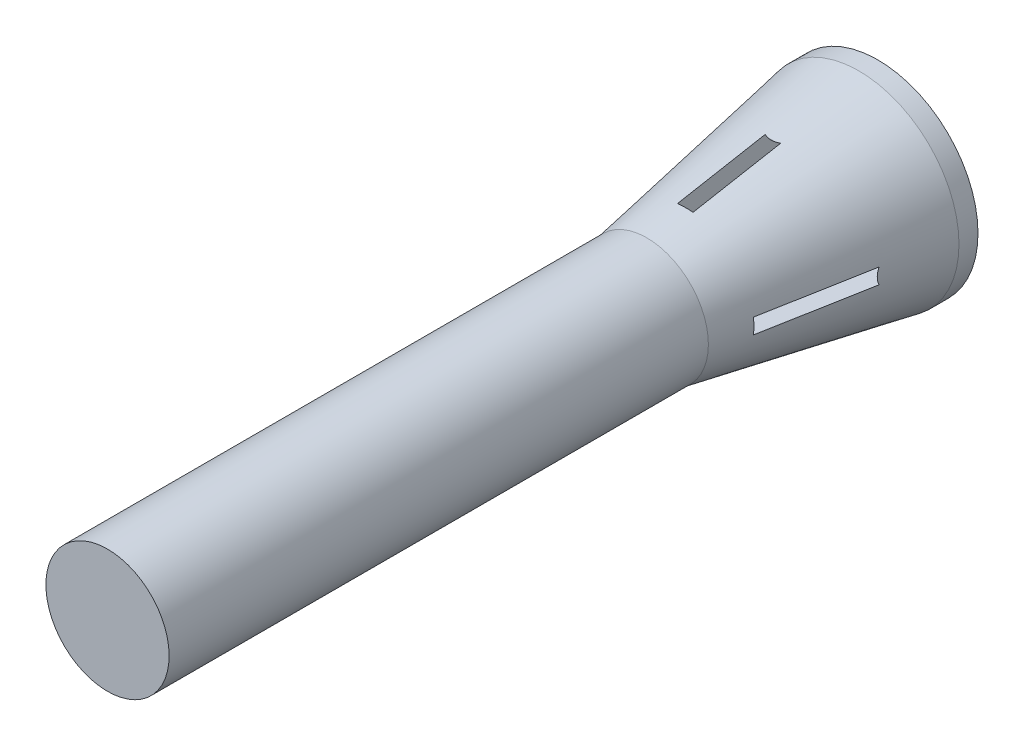
SolidWorks part; units mm, degrees
ref_plane "Plan de face" through (0, 0, 0) normal (0, 0, 1) x (1, 0, 0)
ref_plane "Plan de dessus" through (0, 0, 0) normal (0, 1, 0) x (1, 0, 0)
ref_plane "Plan de droite" through (0, 0, 0) normal (1, 0, 0) x (0, 0, -1)
sketch "Esquisse1" plane through (0, 0, 0) normal (1, 0, 0) x (0, 0, -1)
  line L0 (73.2699, 13.7287) -> (72.0362, 13.7287)
  line L1 (72.0362, 13.7287) -> (58.2699, 11.2287)
  line L2 (58.2699, 11.2287) -> (23.2699, 11.2287)
  line L3 (23.2699, 11.2287) -> (23.2699, 7.2287)
  line L4 (23.2699, 7.2287) -> (63.2699, 7.2287)
  line L5 (63.2699, 7.2287) -> (63.2699, 10.2287)
  line L6 (63.2699, 10.2287) -> (73.2699, 10.2287)
  line L7 (73.2699, 10.2287) -> (73.2699, 13.7287)
  dimension "D1" = 3.5
  dimension "D2" = 3
  dimension "D3" = 50
  dimension "D4" = 15
  dimension "D5" = 4
  dimension "D6" = 40
revolve "Révolution1" add sketch "Esquisse1" angle 360 about L4
sketch "Esquisse12" plane through (0, 0, -73.2699) normal (0, 0, -1) x (-1, 0, 0)
  line L0 (0.5, 7.7287) -> (6.0527, 7.7287)
  line L1 (-0.5, 12.6932) -> (0.5, 12.6932)
  line L2 (-0.5, 12.6932) -> (-0.5, 7.7287)
  line L3 (-0.5, 2.0303) -> (0.5, 2.0303)
  line L4 (0.5, 12.6932) -> (0.5, 7.7287)
  line L5 (-5.6845, 7.7287) -> (-0.5, 7.7287)
  line L6 (-5.6845, 7.7287) -> (-5.6845, 6.7287)
  line L7 (-5.6845, 6.7287) -> (-0.5, 6.7287)
  line L8 (6.0527, 7.7287) -> (6.0527, 6.7287)
  line L9 (-0.5, 6.7287) -> (-0.5, 2.0303)
  line L10 (0.5, 6.7287) -> (6.0527, 6.7287)
  line L11 (0.5, 6.7287) -> (0.5, 2.0303)
  circle A0 centre (0, 7.2287) radius 3 construction
  dimension "D1" = 1
  dimension "D2" = 1
  dimension "D3" = 0.5
  dimension "D4" = 0.5
extrude "Enlèv. mat.-Extru.1" cut sketch "Esquisse12" against normal blind 12.5
